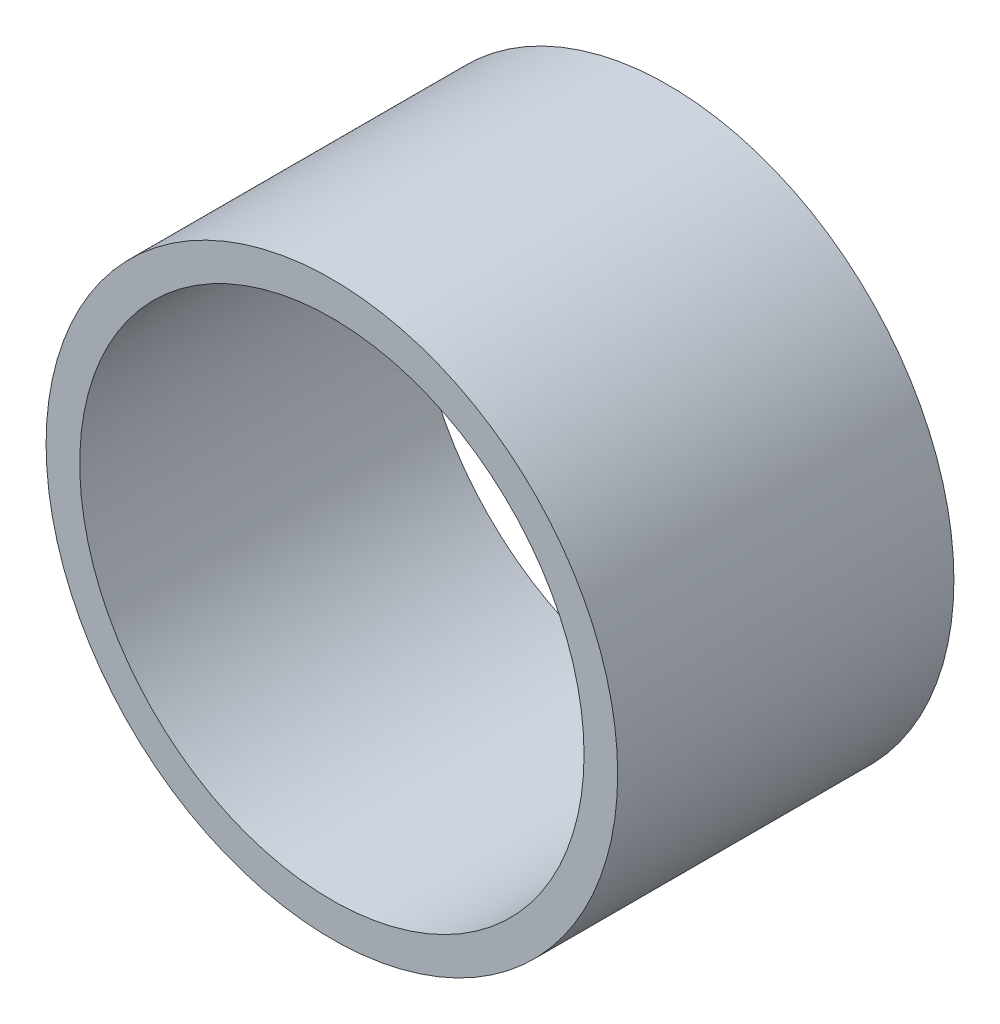
SolidWorks part; units mm, degrees
ref_plane "前视基准面" through (0, 0, 0) normal (0, 0, 1) x (1, 0, 0)
ref_plane "上视基准面" through (0, 0, 0) normal (0, 1, 0) x (1, 0, 0)
ref_plane "右视基准面" through (0, 0, 0) normal (1, 0, 0) x (0, 0, -1)
other "Configuration Table"
sketch "草图1" plane through (0, 0, 0) normal (0, 0, 1) x (1, 0, 0)
  circle A0 centre (0, 0) radius 7.5
  circle A1 centre (0, 0) radius 8.5
  dimension "D1" = 15
  dimension "D2" = 17
extrude "凸台-拉伸1" add sketch "草图1" along normal blind 10
